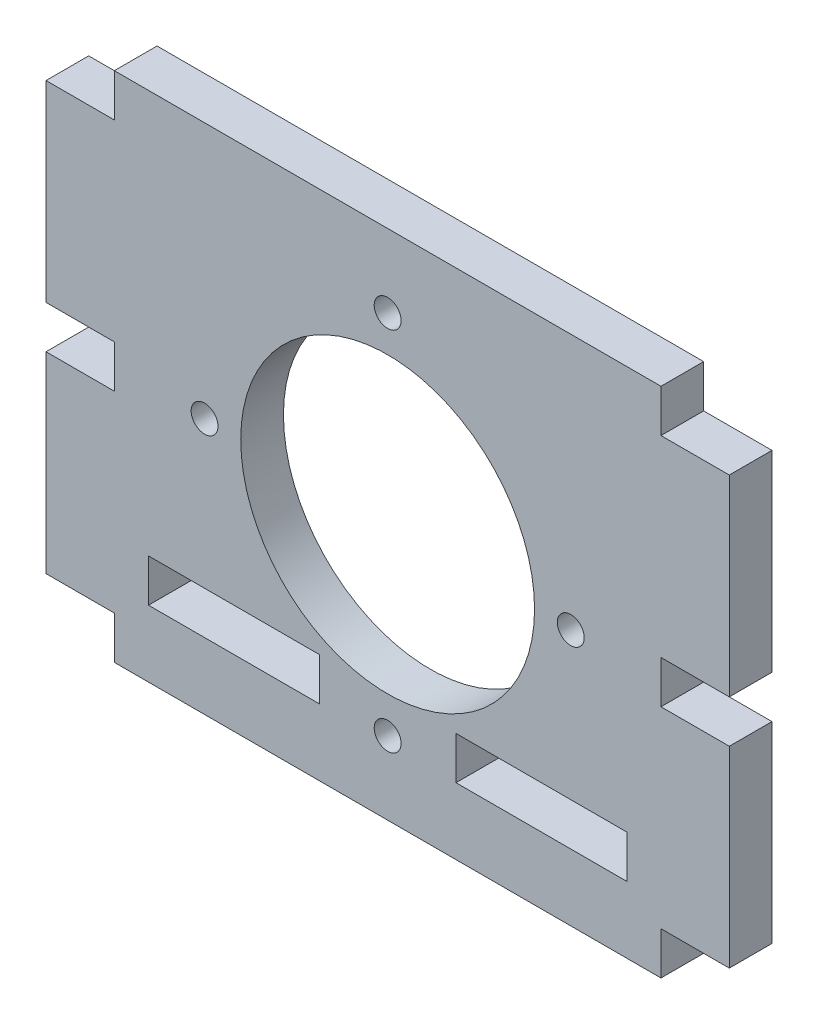
SolidWorks part; units mm, degrees
material "Balsa"
ref_plane "Front Plane" through (0, 0, 0) normal (0, 0, 1) x (1, 0, 0)
ref_plane "Top Plane" through (0, 0, 0) normal (0, 1, 0) x (1, 0, 0)
ref_plane "Right Plane" through (0, 0, 0) normal (1, 0, 0) x (0, 0, -1)
sketch "Sketch3" plane through (0, 0, 0) normal (0, 0, 1) x (1, 0, 0)
  line L1 (-20.32, -19.05) -> (20.32, -19.05)
  line L2 (-20.32, 19.05) -> (20.32, 19.05)
  line L4 (-25.4, 1.5875) -> (-20.32, 1.5875)
  line L5 (25.4, -1.5875) -> (20.32, -1.5875)
  line L6 (0, 19.05) -> (0, -19.05) construction
  line L12 (20.32, 19.05) -> (20.32, 15.875)
  line L13 (20.32, 15.875) -> (25.4, 15.875)
  line L14 (-25.4, 0) -> (25.4, 0) construction
  line L15 (20.32, -15.875) -> (25.4, -15.875)
  line L17 (-5.08, -14.097) -> (-17.78, -14.097)
  line L18 (5.08, -14.097) -> (17.78, -14.097)
  line L19 (5.08, -14.097) -> (5.08, -10.922)
  line L20 (5.08, -10.922) -> (17.78, -10.922)
  line L21 (17.78, -14.097) -> (17.78, -10.922)
  line L22 (-17.78, -14.097) -> (-17.78, -10.922)
  line L23 (-5.08, -10.922) -> (-17.78, -10.922)
  line L24 (-5.08, -14.097) -> (-5.08, -10.922)
  line L25 (0, -13.6118) -> (0, 0) construction
  line L26 (-13.6118, 0) -> (0, 0) construction
  line L27 (0, 0) -> (0, 13.6118) construction
  line L28 (0, 0) -> (13.6118, 0) construction
  line L29 (20.32, -19.05) -> (20.32, -15.875)
  line L30 (-20.32, -19.05) -> (-20.32, -15.875)
  line L32 (-20.32, -15.875) -> (-25.4, -15.875)
  line L33 (-20.32, 15.875) -> (-25.4, 15.875)
  line L34 (-20.32, 19.05) -> (-20.32, 15.875)
  line L37 (-25.4, -15.875) -> (-25.4, 15.875)
  line L38 (25.4, -15.875) -> (25.4, 15.875)
  line L40 (0, 0) -> (13.6118, 0) construction
  line L42 (25.4, -1.5875) -> (25.4, 1.5875)
  line L43 (25.4, 1.5875) -> (20.32, 1.5875)
  line L44 (20.32, -1.5875) -> (20.32, 1.5875)
  line L45 (-20.32, -1.5875) -> (-20.32, 1.5875)
  line L46 (-25.4, -1.5875) -> (-20.32, -1.5875)
  line L47 (-25.4, -1.5875) -> (-25.4, 1.5875)
  circle A5 centre (13.6118, 0) radius 1
  circle A9 centre (0, 0) radius 10.922 construction
  circle A10 centre (0, 0) radius 10.922
  circle A11 centre (0, -13.6118) radius 1
  circle A12 centre (-13.6118, 0) radius 1
  circle A13 centre (0, 13.6118) radius 1
  point P1 (0, 0)
  point P10 (11.43, -14.097)
  point P15 (20.32, 0)
  point P18 (-11.43, -14.097)
  point P31 (13.6118, 0)
  point P47 (25.4, 0)
  point P48 (0, 0)
  dimension "D6" = 4
  dimension "D11" = 13.6118
  dimension "D15" = 2
  dimension "D13" = 7.62
  dimension "D2" = 50.8
  dimension "D3" = 12.7
  dimension "D4" = 3.175
  dimension "D5" = 38.1
  dimension "D7" = 5.08
  dimension "D8" = 3.175
  dimension "D9" = 10.922
  dimension "D10" = 13.6118
extrude "Boss-Extrude1" add sketch "Sketch3" along normal blind 3.175
